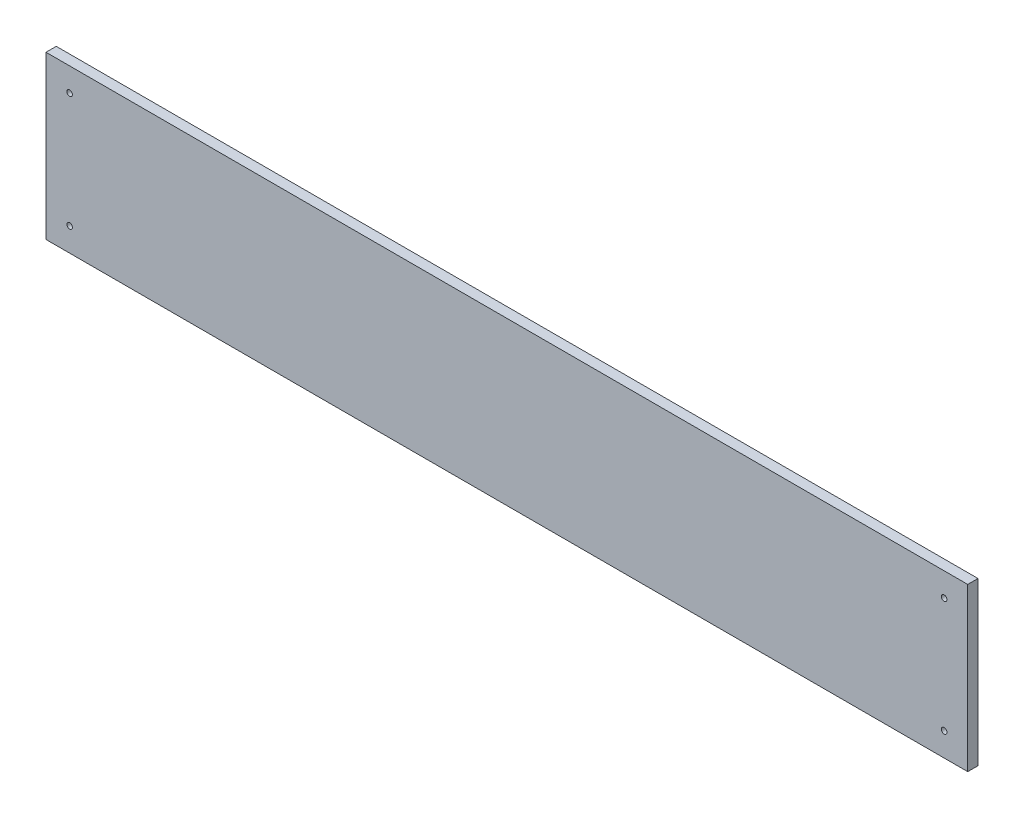
SolidWorks part; units mm, degrees
material "PMMA"
ref_plane "Piano frontale" through (0, 0, 0) normal (0, 0, 1) x (1, 0, 0)
ref_plane "Piano superiore" through (0, 0, 0) normal (0, 1, 0) x (1, 0, 0)
ref_plane "Piano destro" through (0, 0, 0) normal (1, 0, 0) x (0, 0, -1)
sketch "f" plane through (0, 0, 0) normal (0, 0, 1) x (1, 0, 0)
  line L0 (0, 0) -> (0, 79)
  line L1 (0, 79) -> (449, 79)
  line L2 (449, 79) -> (449, 0)
  line L3 (449, 0) -> (0, 0)
  line L4 (0, 39.5) -> (449, 39.5) construction
  line L5 (224.5, 42) -> (224.5, 123.488) construction
  line L10 (449, 79) -> (224.5, 0) construction
  line L11 (334, 39.5) -> (334, 81.5) construction
  line L12 (224.5, 0) -> (0, 79) construction
  line L13 (112.25, 42) -> (112.25, 84) construction
  circle A0 centre (11.5, 67.5) radius 1.3617
  circle A1 centre (437.5, 67.5) radius 1.3617
  circle A2 centre (11.5, 11.5) radius 1.3617
  circle A3 centre (437.5, 11.5) radius 1.3617
  dimension "D3" = 11.5
  dimension "D4" = 11.5
  dimension "D1" = 79
  dimension "D2" = 449
extrude "Estrusione-Estrusione1" add sketch "f" along normal blind 5
